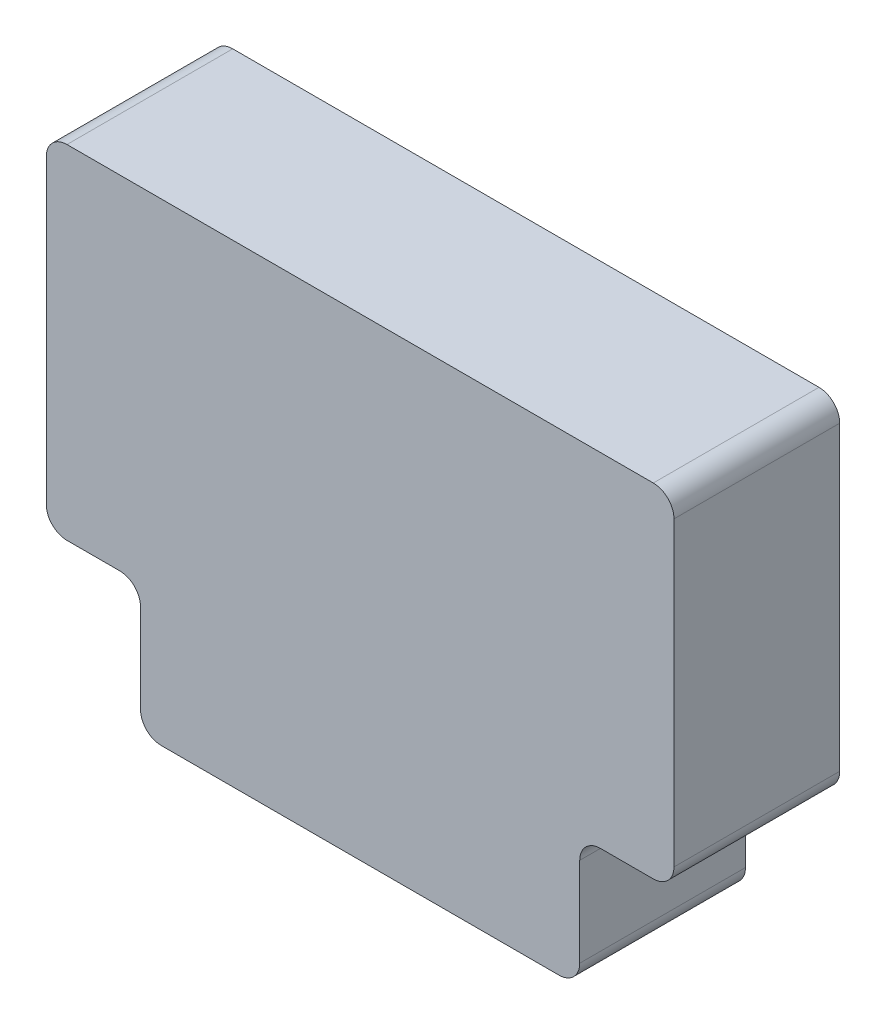
SolidWorks part; units mm, degrees
ref_plane "Płaszczyzna przednia" through (0, 0, 0) normal (0, 0, 1) x (1, 0, 0)
ref_plane "Płaszczyzna górna" through (0, 0, 0) normal (0, 1, 0) x (1, 0, 0)
ref_plane "Płaszczyzna prawa" through (0, 0, 0) normal (1, 0, 0) x (0, 0, -1)
sketch "Szkic1" plane through (0, 0, 0) normal (0, 0, 1) x (1, 0, 0)
  line L0 (0, 0) -> (0, 60.2)
  line L1 (0, 60.2) -> (115.2, 60.2)
  line L2 (115.2, 60.2) -> (115.2, 0)
  line L3 (115.2, 0) -> (97, 0)
  line L4 (97, 0) -> (97, -25.2)
  line L5 (97, -25.2) -> (18.2, -25.2)
  line L6 (18.2, -25.2) -> (18.2, 0)
  line L7 (18.2, 0) -> (0, 0)
  line L8 (-1.4565, 63.2) -> (118.2, 63.2)
  line L9 (118.2, 63.2) -> (118.2, -3)
  line L10 (118.2, -3) -> (100, -3)
  line L11 (100, -3) -> (100, -28.2)
  line L12 (100, -28.2) -> (15.2, -28.2)
  line L13 (15.2, -28.2) -> (15.2, -3)
  line L14 (15.2, -3) -> (-3, -3)
  line L15 (-3, -3) -> (-3, 63.2)
  line L16 (-3, 63.2) -> (-1.4565, 63.2)
  point P17 (109.1, -3)
  dimension "D1" = 18.2
  dimension "D2" = 115.2
  dimension "D3" = 60.2
  dimension "D4" = 25.2
  dimension "D5" = 3
  dimension "D6" = 3
  dimension "D7" = 3
  dimension "D8" = 3
  dimension "D9" = 3
  dimension "D10" = 3
  dimension "D11" = 3
  dimension "D12" = 3
extrude "Dodanie-wyciągnięcie1" add sketch "Szkic1" along normal blind 29
sketch "Szkic2" plane through (0, 0, 29) normal (0, 0, 1) x (1, 0, 0)
  line L0 (-3, 63.2) -> (-3, -3)
  line L1 (-3, -3) -> (15.2, -3)
  line L2 (15.2, -3) -> (15.2, -28.2)
  line L3 (15.2, -28.2) -> (100, -28.2)
  line L4 (100, -28.2) -> (100, -3)
  line L5 (100, -3) -> (118.2, -3)
  line L6 (118.2, -3) -> (118.2, 63.2)
  line L7 (118.2, 63.2) -> (-3, 63.2)
extrude "Dodanie-wyciągnięcie2" add sketch "Szkic2" along normal blind 3
sketch "Szkic3" plane through (0, 0, 29) normal (0, 0, -1) x (-1, 0, 0)
  line L0 (-115.2, 0) -> (-111.2, 4) construction
  line L1 (-115.2, 60.2) -> (-111.2, 56.2) construction
  line L2 (0, 60.2) -> (-3.9013, 56.1037) construction
  line L3 (0, 0) -> (-4.0963, 3.9013) construction
  circle A0 centre (-111.2, 4) radius 3
  circle A1 centre (-111.2, 4) radius 1.5
  circle A2 centre (-111.2, 56.2) radius 1.5
  circle A3 centre (-3.9013, 56.1037) radius 1.5
  circle A4 centre (-4.0963, 3.9013) radius 1.5
  circle A5 centre (-111.2, 56.2) radius 3
  circle A6 centre (-3.9013, 56.1037) radius 3
  circle A7 centre (-4.0963, 3.9013) radius 3
  dimension "D3" = 6
  dimension "D4" = 3
  dimension "D1" = 4
  dimension "D2" = 4
extrude "Dodanie-wyciągnięcie3" add sketch "Szkic3" along normal blind 22
sketch "Szkic5" plane through (0, 0, 0) normal (0, 0, -1) x (-1, 0, 0)
  line L0 (-97, -25.2) -> (-18.2, -25.2) construction
  line L1 (-15.2, -28.2) -> (-100, -28.2) construction
  line L2 (-64.1, -22.2) -> (-51.1, -22.2)
  line L3 (-64.1, -22.2) -> (-64.1, -28.2)
  line L4 (-64.1, -28.2) -> (-51.1, -28.2)
  line L5 (-51.1, -22.2) -> (-51.1, -28.2)
  line L6 (-64.1, -22.2) -> (-51.1, -28.2) construction
  line L7 (-64.1, -28.2) -> (-51.1, -22.2) construction
  point P4 (-57.6, -25.2)
  dimension "D1" = 13
extrude "Wytnij-wyciągnięcie1" cut sketch "Szkic5" against normal blind 7
fillet "Zaokrąglenie1" radius 4 6 edges at (118.2, -3, 16) (118.2, 63.2, 16) (-3, 63.2, 16) (-3, -3, 16) (15.2, -28.2, 16) (100, -28.2, 16)
fillet "Zaokrąglenie2" radius 4 2 edges at (15.2, -3, 16) (100, -3, 16)
